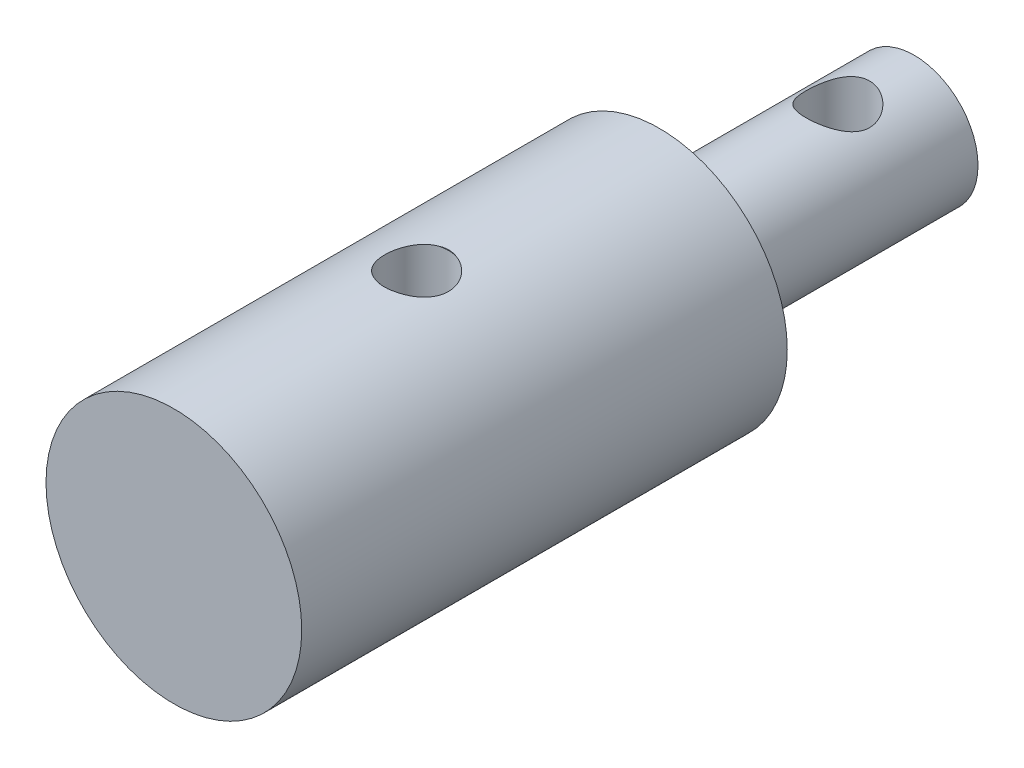
SolidWorks part; units mm, degrees
ref_plane "Front Plane" through (0, 0, 0) normal (0, 0, 1) x (1, 0, 0)
ref_plane "Top Plane" through (0, 0, 0) normal (0, 1, 0) x (1, 0, 0)
ref_plane "Right Plane" through (0, 0, 0) normal (1, 0, 0) x (0, 0, -1)
sketch "Sketch1" plane through (0, 0, 0) normal (0, 0, 1) x (1, 0, 0)
  circle A0 centre (0, 0) radius 5
  dimension "D1" = 10
extrude "Boss-Extrude1" add sketch "Sketch1" along normal blind 20
sketch "Sketch2" plane through (0, 0, 20) normal (0, 0, 1) x (1, 0, 0)
  circle A0 centre (0, 0) radius 10.033
  dimension "D1" = 20.066
extrude "Boss-Extrude2" add sketch "Sketch2" along normal blind 38.1
sketch "Sketch3" plane through (0, 0, 58.1) normal (0, 0, 1) x (1, 0, 0)
  line L1 (0, 10.033) -> (0, 0)
  circle A1 centre (0, 0) radius 10.033 construction
ref_plane "Plane1" through (0, 10.033, 0) normal (0, 1, 0) x (1, 0, 0)
sketch "Sketch4" plane through (0, 10.033, 0) normal (0, 1, 0) x (1, 0, 0)
  line L0 (0, -20) -> (0, -76.3133) construction
  line L1 (10.033, -20) -> (-10.033, -20) construction
  line L2 (0, -20) -> (0, -6)
  line L3 (0, -20) -> (0, -39.05)
  dimension "D1" = 14
  dimension "D2" = 19.05
hole_wizard "Ø5.0mm Dowel Hole1" positions "Sketch7" profile "Sketch8" hole size "Ø5.0" standard "ANSI Metric" end condition through all
sketch "Sketch7" plane through (0, 10.033, 0) normal (0, 1, 0) x (1, 0, 0)
  point P0 (0, -6)
  point P3 (0, -39.05)
sketch "Sketch8" plane through (0, 10.033, 6) normal (1, 0, 0) x (0, 0, 1)
  line L0 (0, 0) -> (0, 20.066)
  line L1 (0, 20.066) -> (2.5, 20.066)
  line L2 (2.5, 20.066) -> (2.5, 0.025)
  line L3 (2.5, 0.025) -> (2.525, 0)
  line L5 (2.525, 0) -> (0, 0)
  line L6 (-2.5, 0.025) -> (-2.525, 0) construction
  line L11 (0, -6.35) -> (0, 107.95) construction
  dimension "Thru Hole Dia." = 5
  dimension "Thru Hole Depth" = 20.066
  dimension "Near C'Sink Dia." = 5.05
  dimension "Near C'Sink Angle" = 90
